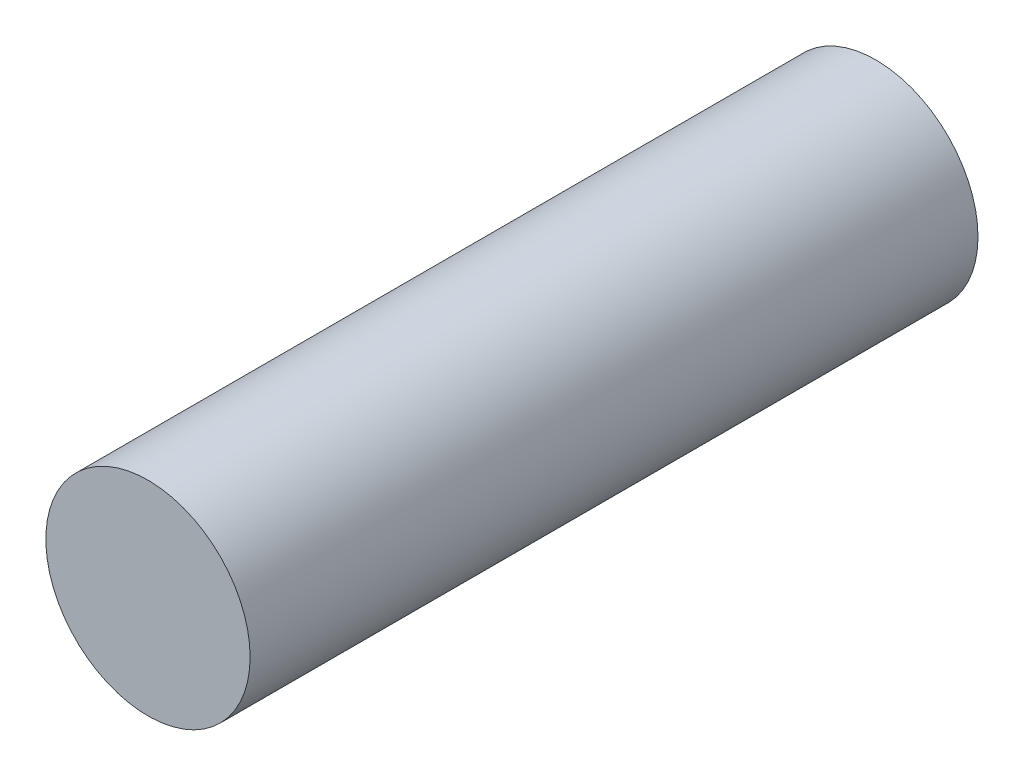
SolidWorks part; units mm, degrees
ref_plane "Front Plane" through (0, 0, 0) normal (1, 0, 0) x (0, 1, 0)
ref_plane "Top Plane" through (0, 0, 0) normal (0, 0, 1) x (0, 1, 0)
ref_plane "Right Plane" through (0, 0, 0) normal (0, 1, 0) x (-1, 0, 0)
sketch "Sketch1" plane through (0, 0, 0) normal (0, 0, 1) x (0, 1, 0)
  circle A0 centre (0, 0) radius 9
extrude "Boss-Extrude1" add sketch "Sketch1" along normal blind 64.14
ref_plane "Plane1" through (0, 9, 0) normal (0, 1, 0) x (-1, 0, 0)
ref_plane "Plane2" through (-9, 0, 0) normal (-1, 0, 0) x (0, -1, 0)
ref_plane "Plane3" through (0, -9, 0) normal (0, -1, 0) x (1, 0, 0)
ref_plane "Plane4" through (9, 0, 0) normal (1, 0, 0) x (0, 1, 0)
sketch "Sketch3" plane through (0, 0, 0) normal (1, 0, 0) x (0, 1, 0)
  line L0 (0, 0) -> (0, 64.14) construction
  line L1 (9, 64.14) -> (-9, 64.14) construction
sketch3d "3DSketch2"
  line L0 (0, 0, 64.14) -> (0, 9, 64.14) construction
  line L1 (0, 0, 64.14) -> (0, 0, 0) construction
  line L2 (0, 9, 64.14) -> (0, 9, 57.57) construction
  line L3 (0, 0, 64.14) -> (9, 0, 64.14) construction
  line L4 (9, 0, 64.14) -> (9, 0, 49.07) construction
  line L5 (0, 9, 57.57) -> (9, 0, 49.07) construction
  line L6 (4.5, 4.5, 53.32) -> (0, 0, 53.32) construction
  line L7 (0, 0, 0) -> (0, 0, 64.14) construction
  circle A0 centre (0, 0, 64.14) radius 9 construction
  circle A1 centre (0, 9, 57.57) radius 5.57 construction
  circle A2 centre (9, 0, 49.07) radius 5.57 construction
  spline S0 degree 2 poles (9, 0, 49.07) (0, 0, 53.32) (0, 9, 57.57) knots 0 0 0 1 1 1
  point P6 (0, 0, 73.14)
  point P11 (0, 14.57, 57.57)
  point P13 (14.57, 0, 49.07)
sketch3d "3DSketch1"
  line L2 (0, 0, 0) -> (9, 0, 0) construction
  line L3 (0, 0, 0) -> (0, -9, 0) construction
  line L4 (9, 0, 0) -> (9, 0, 15.07) construction
  line L5 (0, -9, 0) -> (0, -9, 7.9309) construction
  line L6 (0, -9, 7.9309) -> (9, 0, 15.07) construction
  line L7 (4.5, -4.5, 11.5004) -> (0, 0, 11.5004) construction
  line L8 (0, 0, 0) -> (0, 0, 64.14) construction
  circle A0 centre (0, -9, 7.9309) radius 5.57 construction
  circle A1 centre (0, 0, 0) radius 9 construction
  circle A3 centre (9, 0, 15.07) radius 5.57 construction
  spline S0 degree 2 poles (0, -9, 7.9309) (0, 0, 11.5004) (9, 0, 15.07) knots 0 0 0 1 1 1
  point P5 (0, 0, 9)
  point P10 (0, -3.43, 7.9309)
  point P13 (14.57, 0, 15.07)
sketch3d "3DSketch3"
  line L0 (0, 0, 64.14) -> (0, 9, 64.14) construction
  line L1 (0, 9, 64.14) -> (0, 9, 40.57) construction
  line L2 (0, 0, 64.14) -> (0, -9, 64.14) construction
  line L3 (0, -9, 64.14) -> (0, -9, 40.57) construction
  line L4 (0, -9, 40.57) -> (0, 9, 40.57) construction
  circle A0 centre (0, 0, 64.14) radius 9 construction
  circle A1 centre (0, -9, 40.57) radius 5.57 construction
  circle A2 centre (0, 9, 40.57) radius 5.57 construction
  point P8 (0, 0, 73.14)
  point P11 (0, -3.43, 40.57)
  point P13 (0, 14.57, 40.57)
  dimension "D1" = 23.57
